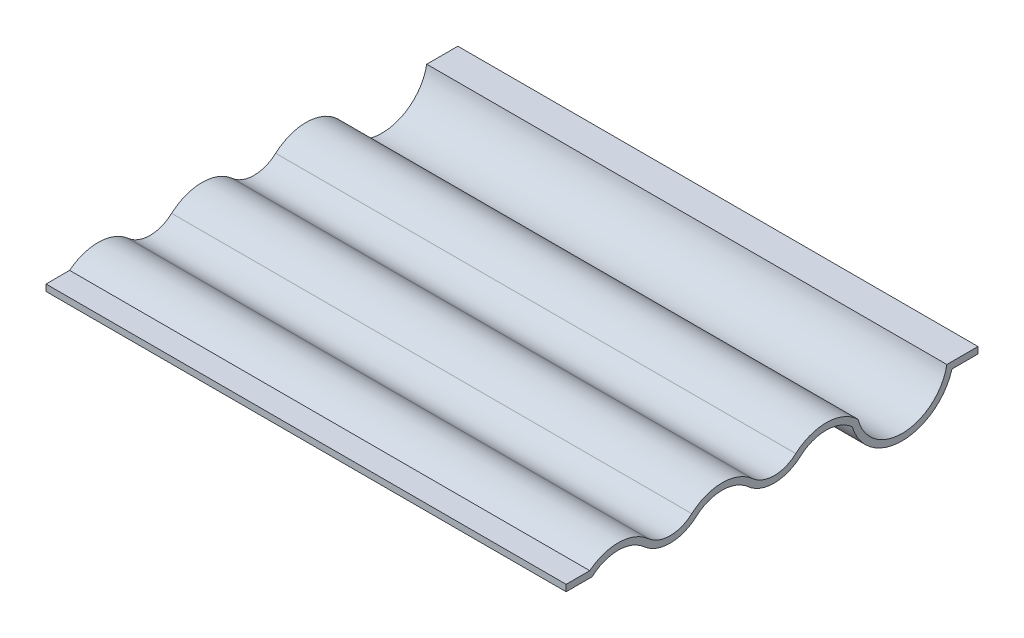
SolidWorks part; units mm, degrees
ref_plane "Front Plane" through (0, 0, 0) normal (0, 0, 1) x (1, 0, 0)
ref_plane "Top Plane" through (0, 0, 0) normal (0, 1, 0) x (1, 0, 0)
ref_plane "Right Plane" through (0, 0, 0) normal (1, 0, 0) x (0, 0, -1)
sketch "Sketch1" plane through (0, 0, 0) normal (1, 0, 0) x (0, 0, -1)
  line L0 (50.1201, 0) -> (-76.8799, 0) construction
  line L1 (-76.8799, 0) -> (-89.5638, 0)
  line L2 (-76.8799, 0) -> (-26.0799, 0) construction
  line L3 (-51.4799, 0) -> (-0.6799, 0) construction
  line L4 (-112.9661, 0) -> (98.8663, 0) construction
  line L5 (98.8663, 0) -> (111.5663, 0)
  line L6 (-78.0397, 3.175) -> (-89.5638, 3.175)
  line L7 (96.36, 3.175) -> (111.5663, 3.175)
  line L8 (-89.5638, 3.175) -> (-89.5638, 0)
  line L9 (111.5663, 3.175) -> (111.5663, 0)
  arc A1 (-76.8799, 0) -> (-51.4799, 0) centre (-64.1799, -14.199) cw
  arc A2 (-26.0799, 0) -> (-0.6799, 0) centre (-13.3799, -14.199) cw
  arc A3 (24.7201, 0) -> (50.1201, 0) centre (37.4201, -14.199) cw
  arc A4 (-51.4799, 0) -> (-26.0799, 0) centre (-38.7799, 14.199) ccw
  arc A5 (-0.6799, 0) -> (24.7201, 0) centre (12.0201, 14.199) ccw
  arc A6 (50.1201, 0) -> (98.8663, 0) centre (74.4932, 7.1492) ccw
  arc A7 (-78.0397, 3.175) -> (-49.3633, 2.3665) centre (-64.1799, -14.199) cw
  arc A8 (-49.3633, 2.3665) -> (-28.1966, 2.3665) centre (-38.7799, 14.199) ccw
  arc A9 (-28.1966, 2.3665) -> (1.4367, 2.3665) centre (-13.3799, -14.199) cw
  arc A10 (1.4367, 2.3665) -> (22.6034, 2.3665) centre (12.0201, 14.199) ccw
  arc A11 (22.6034, 2.3665) -> (52.9455, 1.7041) centre (37.4201, -14.199) cw
  arc A12 (52.9455, 1.7041) -> (96.36, 3.175) centre (74.4932, 7.1492) ccw
  point P4 (-13.3799, 0)
  point P38 (0, 0)
  dimension "D1" = 19.05
  dimension "D4" = 3
  dimension "D6" = 2
  dimension "D5" = 25.4
  dimension "D2" = 127
  dimension "D3" = 25.4
  dimension "D7" = 12.7
  dimension "D8" = 3.175
extrude "Boss-Extrude4" add sketch "Sketch1" along normal blind 254
